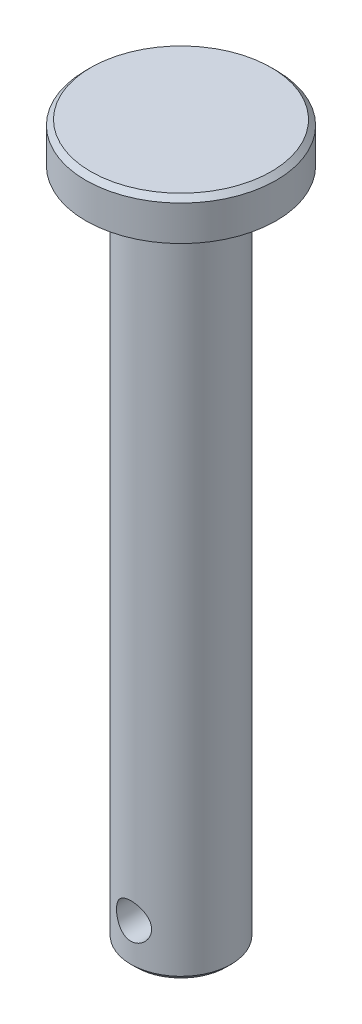
SolidWorks part; units mm, degrees
material "AISI 1020"
ref_plane "Plano frontal" through (0, 0, 0) normal (0, 0, 1) x (1, 0, 0)
ref_plane "Plano superior" through (0, 0, 0) normal (0, 1, 0) x (1, 0, 0)
ref_plane "Plano direito" through (0, 0, 0) normal (1, 0, 0) x (0, 0, -1)
sketch "Esboço1" plane through (0, 0, 0) normal (1, 0, 0) x (0, 0, -1)
  line L0 (0, 71) -> (0, -71) construction
  line L1 (0, 71) -> (18, 71)
  line L2 (19, 70) -> (19, 63)
  line L3 (19, 63) -> (10, 63)
  line L4 (10, 63) -> (10, -70)
  line L5 (9, -71) -> (0, -71)
  line L6 (18, 71) -> (19, 70)
  line L7 (10, -70) -> (9, -71)
  line L8 (0, -71) -> (0, 71)
  point P4 (19, 71)
  point P7 (10, -71)
  point P12 (0, 91.1798)
  dimension "D2" = 20
  dimension "D3" = 38
  dimension "D4" = 8
  dimension "D5" = 142
revolve "Revolução1" add sketch "Esboço1" angle 360 about L0
sketch "Esboço2" plane through (0, 0, 0) normal (0, 0, 1) x (1, 0, 0)
  line L0 (0, -71) -> (0, -62.5) construction
  line L1 (-9, -71) -> (9, -71) construction
  circle A0 centre (0, -62.5) radius 3.5
  dimension "D1" = 7
  dimension "D2" = 8.5
extrude "Corte-extrusão1" cut sketch "Esboço2" against normal through all both and the other way through all
